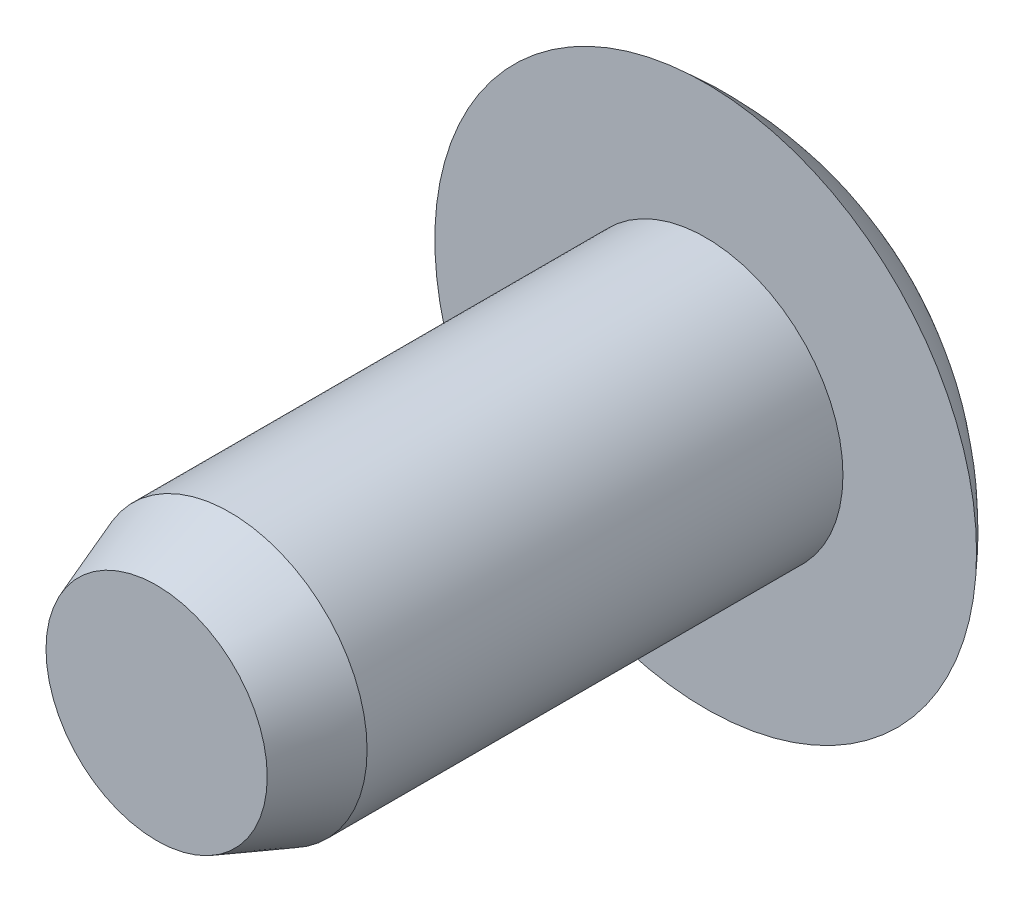
SolidWorks part; units mm, degrees
material "Brass"
ref_plane "Front Plane" through (0, 0, 0) normal (0, 0, 1) x (1, 0, 0)
ref_plane "Top Plane" through (0, 0, 0) normal (0, 1, 0) x (1, 0, 0)
ref_plane "Right Plane" through (0, 0, 0) normal (1, 0, 0) x (0, 0, -1)
sketch "Sketch1" plane through (0, 0, 0) normal (0, 1, 0) x (1, 0, 0)
  line L0 (0, 0) -> (0, 5.842) construction
  line L1 (0, 0) -> (1.1906, 0)
  line L2 (1.1906, 0) -> (1.1906, 4.7625)
  line L3 (1.1906, 4.7625) -> (2.3495, 4.7625)
  line L4 (0, 0) -> (0, 5.842)
  arc A0 (0, 5.842) -> (2.3495, 4.7625) centre (0, 2.7454) cw
  dimension "D1" = 2.3813
  dimension "D2" = 4.7625
  dimension "D3" = 5.842
  dimension "D4" = 4.699
revolve "Revolve1" add sketch "Sketch1" angle 360 about L0
chamfer "Chamfer1" distance 0.635 angle 20 1 edges at (1.1906, 0, 0)
